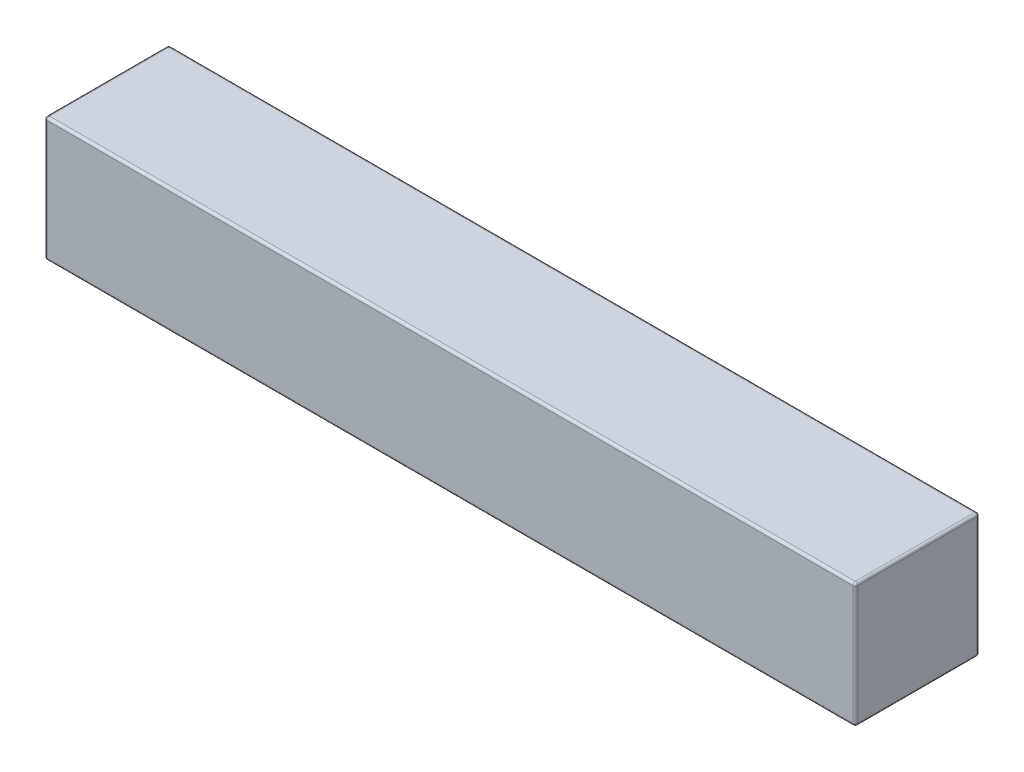
SolidWorks part; units mm, degrees
ref_plane "Front Plane" through (0, 0, 0) normal (0, 0, 1) x (1, 0, 0)
ref_plane "Top Plane" through (0, 0, 0) normal (0, 1, 0) x (1, 0, 0)
ref_plane "Right Plane" through (0, 0, 0) normal (1, 0, 0) x (0, 0, -1)
sketch "Sketch1" plane through (0, 0, 0) normal (0, 0, 1) x (1, 0, 0)
  line L1 (0, 0) -> (130.6, 0)
  line L2 (0, 0) -> (0, -20)
  line L3 (0, -20) -> (130.6, -20)
  line L4 (130.6, 0) -> (130.6, -20)
  dimension "D1" = 130.6
  dimension "D2" = 20
extrude "Boss-Extrude1" add sketch "Sketch1" along normal blind 20
fillet "Fillet1" radius 0.4 12 edges at (0, 0, 10) (0, -20, 10) (130.6, -20, 10) (130.6, 0, 10) (65.3, -20, 0) (130.6, -10, 0) (65.3, 0, 0) (0, -10, 0) (65.3, 0, 20) (130.6, -10, 20) (65.3, -20, 20) (0, -10, 20)
sketch "Sketch2" plane through (0, 0, 0) normal (0, 0, -1) x (-1, 0, 0)
  text T0 "<b>130</b>" font "Gill Sans Ultra Bold" height in points 48
extrude "Cut-Extrude1" cut sketch "Sketch2" against normal blind 0.6
